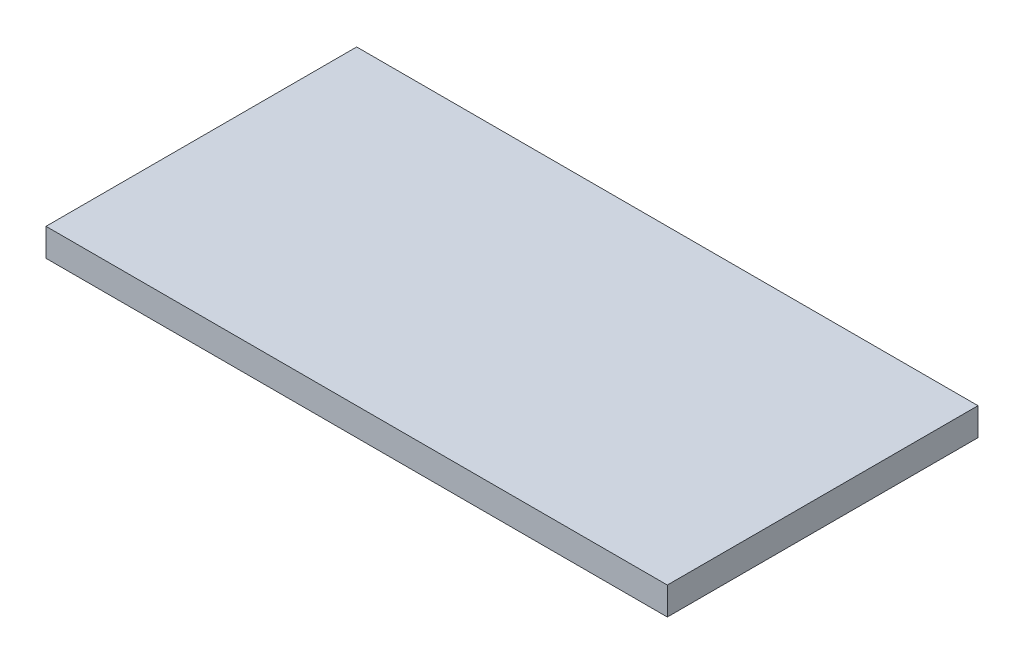
SolidWorks part; units mm, degrees
ref_plane "Front Plane" through (0, 0, 0) normal (0, 0, 1) x (1, 0, 0)
ref_plane "Top Plane" through (0, 0, 0) normal (0, 1, 0) x (1, 0, 0)
ref_plane "Right Plane" through (0, 0, 0) normal (1, 0, 0) x (0, 0, -1)
sketch "Sketch1" plane through (0, 0, 0) normal (0, 1, 0) x (1, 0, 0)
  line L1 (0, 0) -> (35.56, 0)
  line L2 (0, 0) -> (0, 17.78)
  line L3 (0, 17.78) -> (35.56, 17.78)
  line L4 (35.56, 0) -> (35.56, 17.78)
  dimension "D1" = 17.78
  dimension "D2" = 35.56
extrude "Boss-Extrude1" add sketch "Sketch1" along normal blind 1.5875
